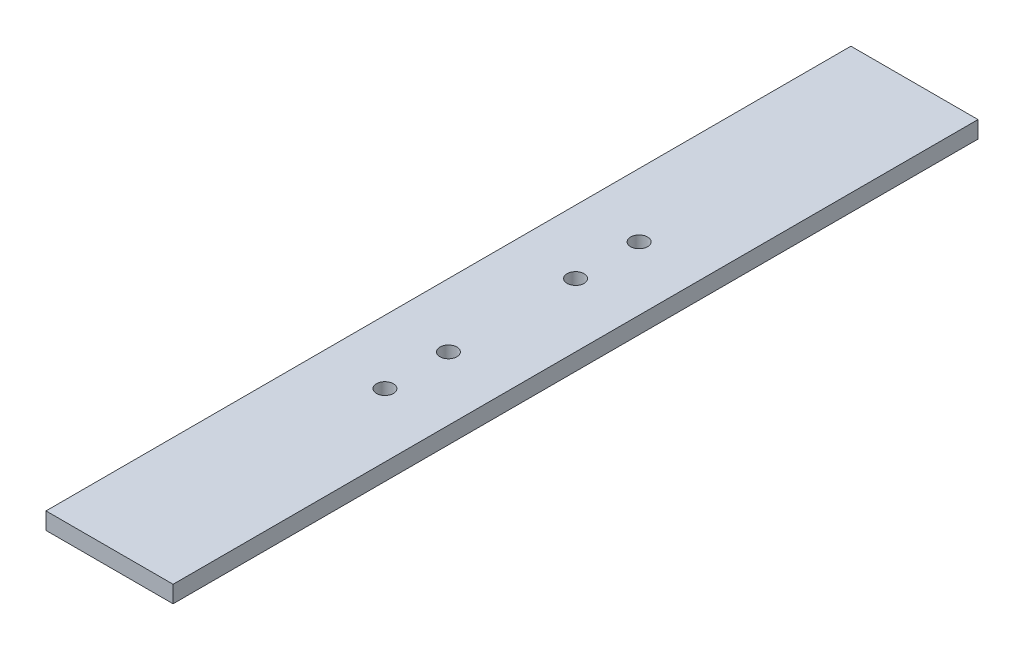
SolidWorks part; units mm, degrees
ref_plane "Front Plane" through (0, 0, 0) normal (0, 0, 1) x (1, 0, 0)
ref_plane "Top Plane" through (0, 0, 0) normal (0, 1, 0) x (1, 0, 0)
ref_plane "Right Plane" through (0, 0, 0) normal (1, 0, 0) x (0, 0, -1)
sketch "Sketch1" plane through (0, 0, 0) normal (0, 1, 0) x (1, 0, 0)
  line L0 (-65, 47.5) -> (-50, 47.5)
  line L1 (-65, 47.5) -> (-65, -47.5)
  line L2 (-65, -47.5) -> (-50, -47.5)
  line L3 (-50, 47.5) -> (-50, -47.5)
  line L4 (-50, 0) -> (-65, 0) construction
  line L5 (-57.5, 0) -> (-57.5, 17.1397) construction
  line L6 (0, -9.9434) -> (0, 0) construction
  line L7 (-57.5, 17.1397) -> (-57.5, -39.6729) construction
  circle A0 centre (-57.5, 15) radius 1
  circle A1 centre (-57.5, -7.5) radius 1
  circle A2 centre (-57.5, -15) radius 1
  circle A3 centre (-57.5, 7.5) radius 1
  dimension "D2" = 2
  dimension "D3" = 2
  dimension "D4" = 2
  dimension "D5" = 2
  dimension "D10" = 7.5
  dimension "D11" = 7.5
  dimension "D1" = 15
  dimension "D6" = 7.5
  dimension "D7" = 7.5
  dimension "D8" = 95
  dimension "D9" = 50
extrude "Boss-Extrude1" add sketch "Sketch1" along normal blind 2
